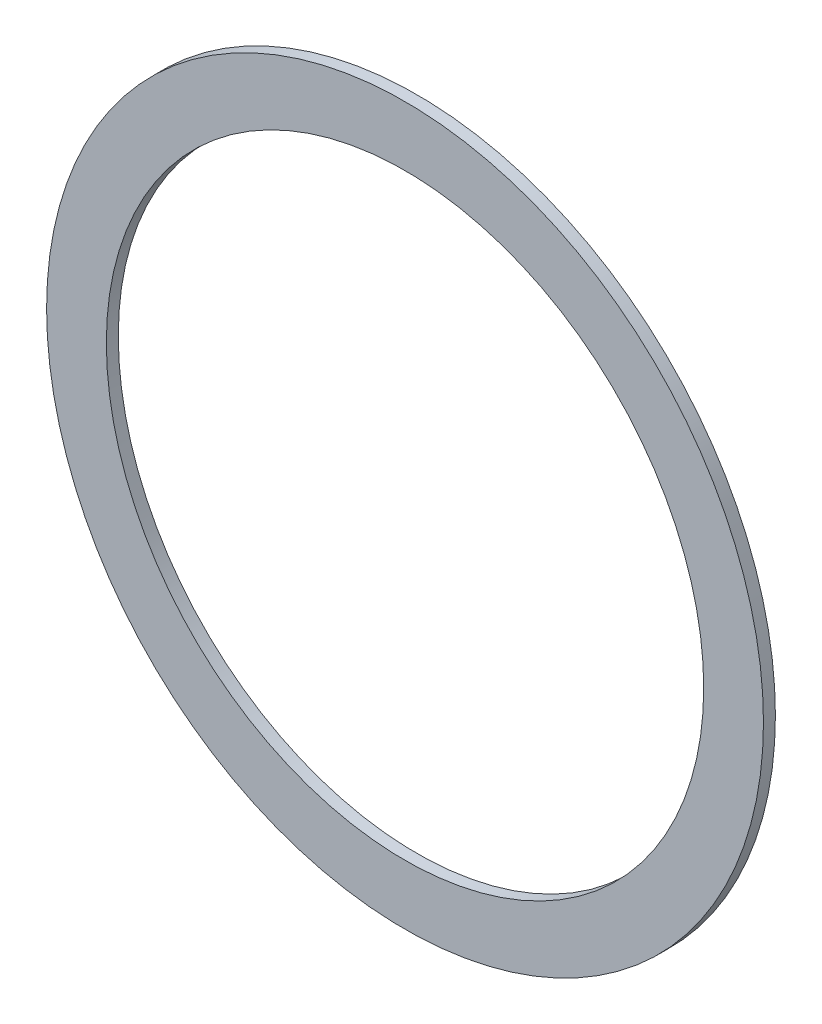
SolidWorks part; units mm, degrees
ref_plane "前视基准面" through (0, 0, 0) normal (0, 0, 1) x (1, 0, 0)
ref_plane "上视基准面" through (0, 0, 0) normal (0, 1, 0) x (1, 0, 0)
ref_plane "右视基准面" through (0, 0, 0) normal (1, 0, 0) x (0, 0, -1)
sketch "草图1" plane through (0, 0, 0) normal (0, 0, 1) x (1, 0, 0)
  circle A0 centre (0, 0) radius 5
  circle A1 centre (0, 0) radius 6
  dimension "D1" = 10
  dimension "D2" = 12
extrude "凸台-拉伸1" add sketch "草图1" along normal mid plane 0.2
